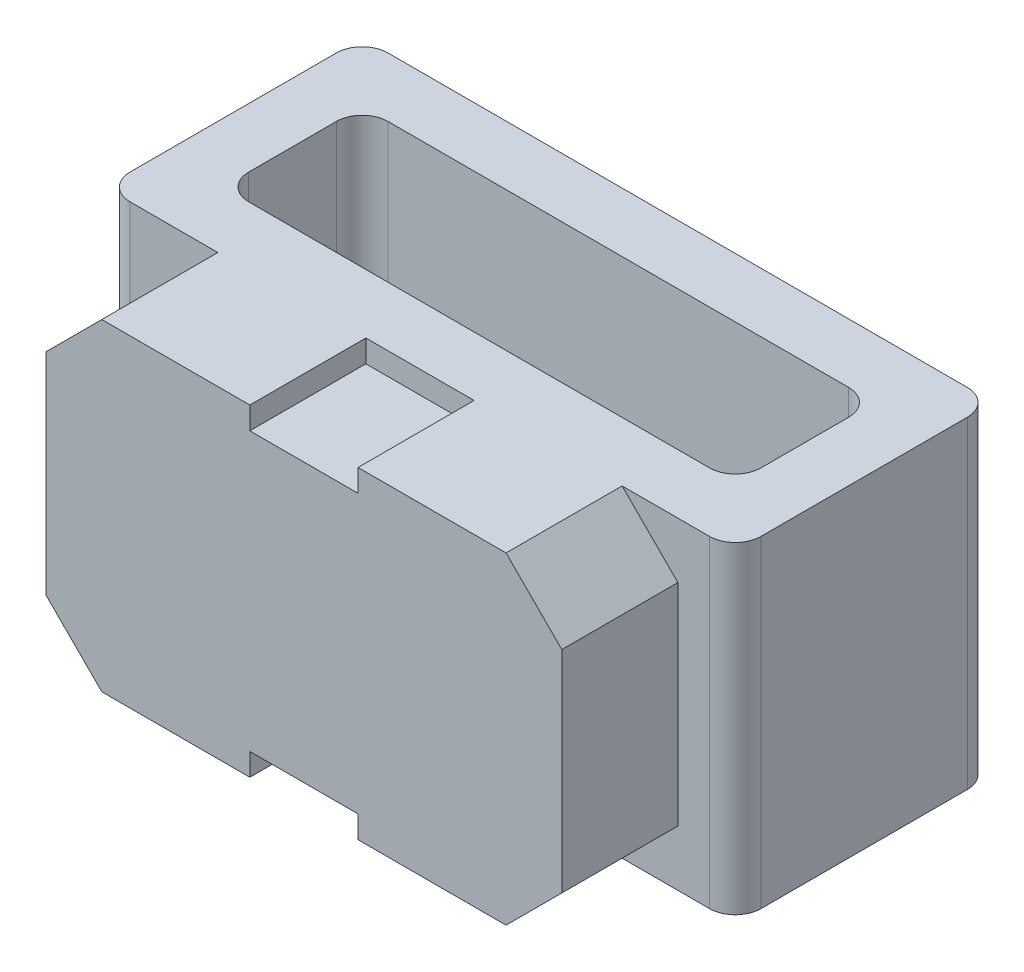
SolidWorks part; units mm, degrees
ref_plane "Front Plane" through (0, 0, 0) normal (0, 0, 1) x (1, 0, 0)
ref_plane "Top Plane" through (0, 0, 0) normal (0, 1, 0) x (1, 0, 0)
ref_plane "Right Plane" through (0, 0, 0) normal (1, 0, 0) x (0, 0, -1)
sketch "Sketch2" plane through (0, 0, 0) normal (0, 0, 1) x (1, 0, 0)
  line L0 (0, 0) -> (0, 0.625) construction
  line L1 (0, 0) -> (-1, 0) construction
  line L2 (-1, -0.4087) -> (-1, 0.4087)
  line L3 (-1, 0.4087) -> (-0.7837, 0.625)
  line L4 (-0.7837, 0.625) -> (-0.2098, 0.625)
  line L5 (-0.2098, 0.625) -> (-0.2098, 0.5383)
  line L6 (-0.2098, 0.5383) -> (0.2098, 0.5383)
  line L7 (0.2098, 0.625) -> (0.2098, 0.5383)
  line L8 (0.7837, 0.625) -> (0.2098, 0.625)
  line L9 (1, 0.4087) -> (0.7837, 0.625)
  line L10 (1, -0.4087) -> (1, 0.4087)
  line L11 (1, -0.4087) -> (0.7837, -0.625)
  line L12 (0.7837, -0.625) -> (0.2098, -0.625)
  line L13 (0.2098, -0.625) -> (0.2098, -0.5383)
  line L14 (-0.2098, -0.5383) -> (0.2098, -0.5383)
  line L15 (-0.2098, -0.625) -> (-0.2098, -0.5383)
  line L16 (-0.7837, -0.625) -> (-0.2098, -0.625)
  line L17 (-1, -0.4087) -> (-0.7837, -0.625)
  point P10 (0, 0.5383)
  point P15 (1, 0)
  point P22 (0, -0.5383)
  point P23 (-1, 0.4794)
  point P24 (-1, 0.4087)
  point P25 (-0.2098, 0.5383)
  dimension "D1" = 1.25
  dimension "D2" = 2
  dimension "D3" = 135
extrude "Boss-Extrude1" add sketch "Sketch2" along normal blind 0.45
sketch "Sketch3" plane through (0, 0, 0) normal (0, 1, 0) x (1, 0, 0)
  line L0 (0.7837, -0.45) -> (0.2098, -0.45) construction
  line L1 (-0.9941, 0.77) -> (0.9924, 0.77)
  line L2 (-0.9941, 0.77) -> (-0.9941, 0.23)
  line L3 (-0.9941, 0.23) -> (0.9924, 0.23)
  line L4 (0.9924, 0.77) -> (0.9924, 0.23)
  line L5 (-0.9941, 0.77) -> (0.9924, 0.23) construction
  line L6 (-0.9941, 0.23) -> (0.9924, 0.77) construction
  line L7 (-1.2241, 1) -> (1.2224, 1)
  line L8 (-1.2241, 1) -> (-1.2241, 0)
  line L9 (-1.2241, 0) -> (1.2224, 0)
  line L10 (1.2224, 1) -> (1.2224, 0)
  line L11 (-1.2241, 1) -> (1.2224, 0) construction
  line L12 (-1.2241, 0) -> (1.2224, 1) construction
  line L13 (0.7837, 0) -> (0.2098, 0) construction
  point P0 (-0.0009, 0.5)
  point P5 (-0.0009, 0.5)
  dimension "D1" = 0.23
  dimension "D2" = 0.23
  dimension "D3" = 1.45
extrude "Boss-Extrude2" add sketch "Sketch3" along normal mid plane 1.25
fillet "Fillet1" radius 0.1 8 edges at (-0.9941, 0, -0.23) (0.9924, 0, -0.23) (0.9924, 0, -0.77) (-0.9941, 0, -0.77) (1.2224, 0, 0) (-1.2241, 0, 0) (-1.2241, 0, -1) (1.2224, 0, -1)
